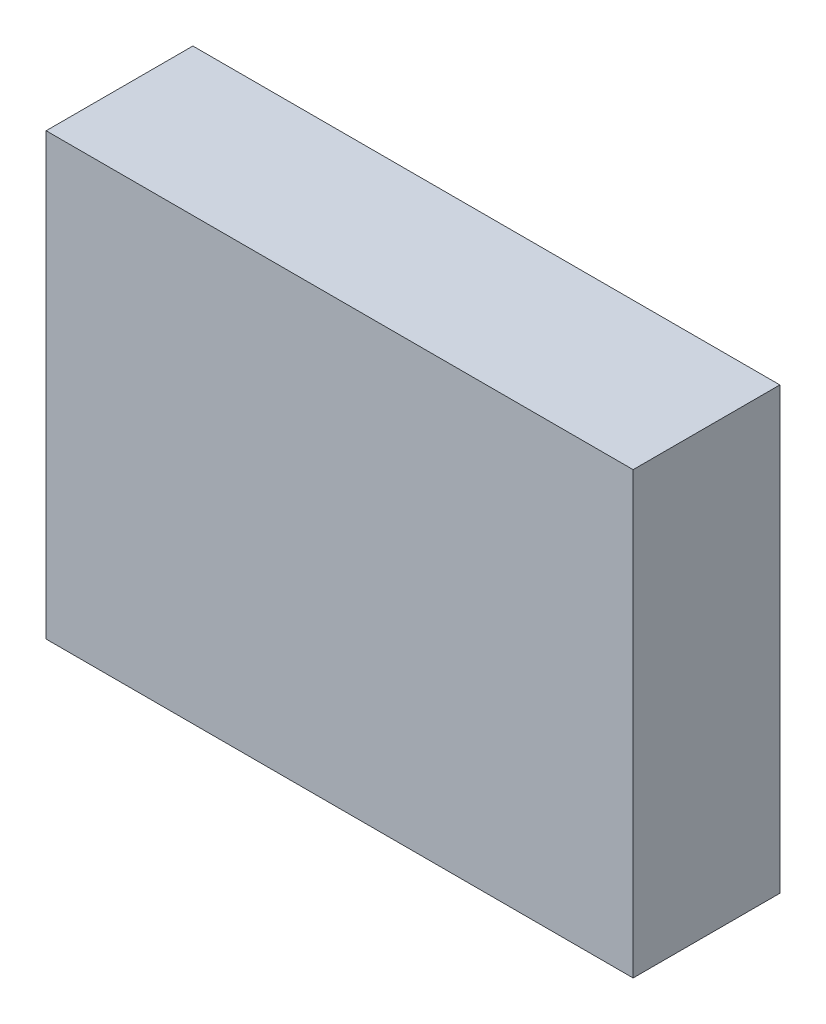
SolidWorks part; units mm, degrees
ref_plane "Front Plane" through (0, 0, 0) normal (0, 0, 1) x (1, 0, 0)
ref_plane "Top Plane" through (0, 0, 0) normal (0, 1, 0) x (1, 0, 0)
ref_plane "Right Plane" through (0, 0, 0) normal (1, 0, 0) x (0, 0, -1)
sketch "Sketch1" plane through (0, 0, 0) normal (0, 0, 1) x (1, 0, 0)
  line L1 (0, 0) -> (40, 0)
  line L2 (0, 0) -> (0, 30)
  line L3 (0, 30) -> (40, 30)
  line L4 (40, 0) -> (40, 30)
extrude "Boss-Extrude1" add sketch "Sketch1" along normal blind 10
